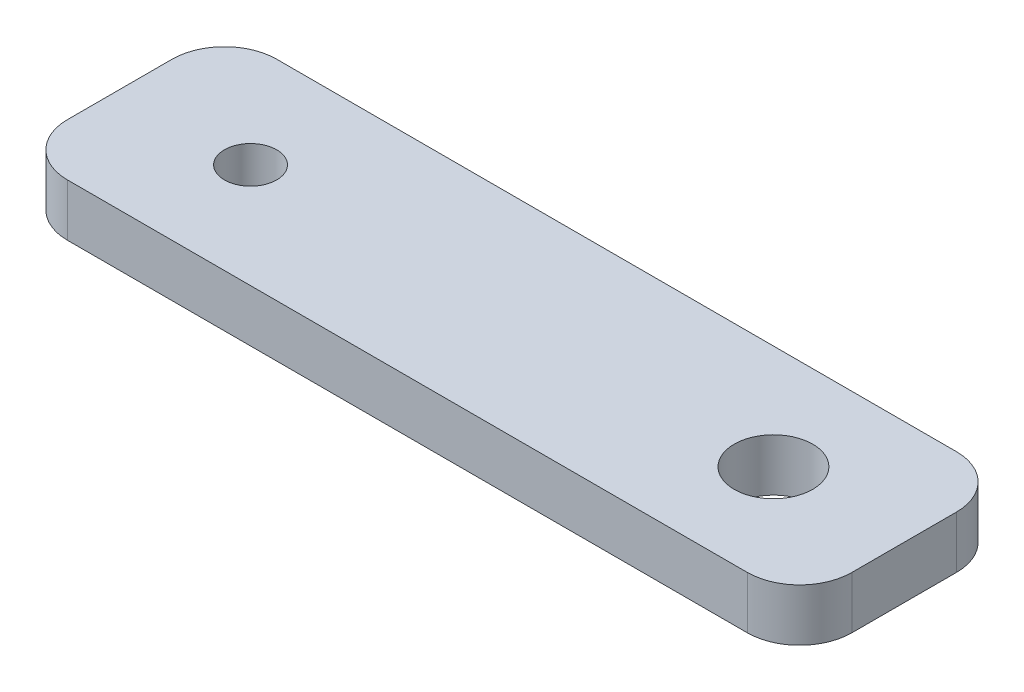
SolidWorks part; units mm, degrees
ref_plane "Front" through (0, 0, 0) normal (0, 0, 1) x (1, 0, 0)
ref_plane "Top" through (0, 0, 0) normal (0, 1, 0) x (1, 0, 0)
ref_plane "Right" through (0, 0, 0) normal (1, 0, 0) x (0, 0, -1)
sketch "Sketch1" plane through (0, 0, 0) normal (0, 1, 0) x (1, 0, 0)
  line L1 (0, 0) -> (30, 0)
  line L2 (0, 0) -> (0, -8)
  line L3 (0, -8) -> (30, -8)
  line L4 (30, 0) -> (30, -8)
  dimension "D1" = 30
  dimension "D2" = 8
extrude "Boss-Extrude1" add sketch "Sketch1" along normal blind 2
sketch "Sketch2" plane through (0, 2, 0) normal (0, 1, 0) x (1, 0, 0)
  line L0 (30, -8) -> (30, 0) construction
  circle A0 centre (25, -4) radius 1.5
  dimension "D1" = 3
  dimension "D2" = 5
extrude "Cut-Extrude1" cut sketch "Sketch2" against normal through all
sketch "Sketch3" plane through (0, 2, 0) normal (0, 1, 0) x (1, 0, 0)
  line L0 (0, 0) -> (0, -8) construction
  circle A0 centre (5, -4) radius 1
  dimension "D1" = 2
  dimension "D2" = 5
extrude "Cut-Extrude2" cut sketch "Sketch3" against normal through all
fillet "Fillet1" radius 2 4 edges at (30, 1, 0) (30, 1, 8) (0, 1, 8) (0, 1, 0)
